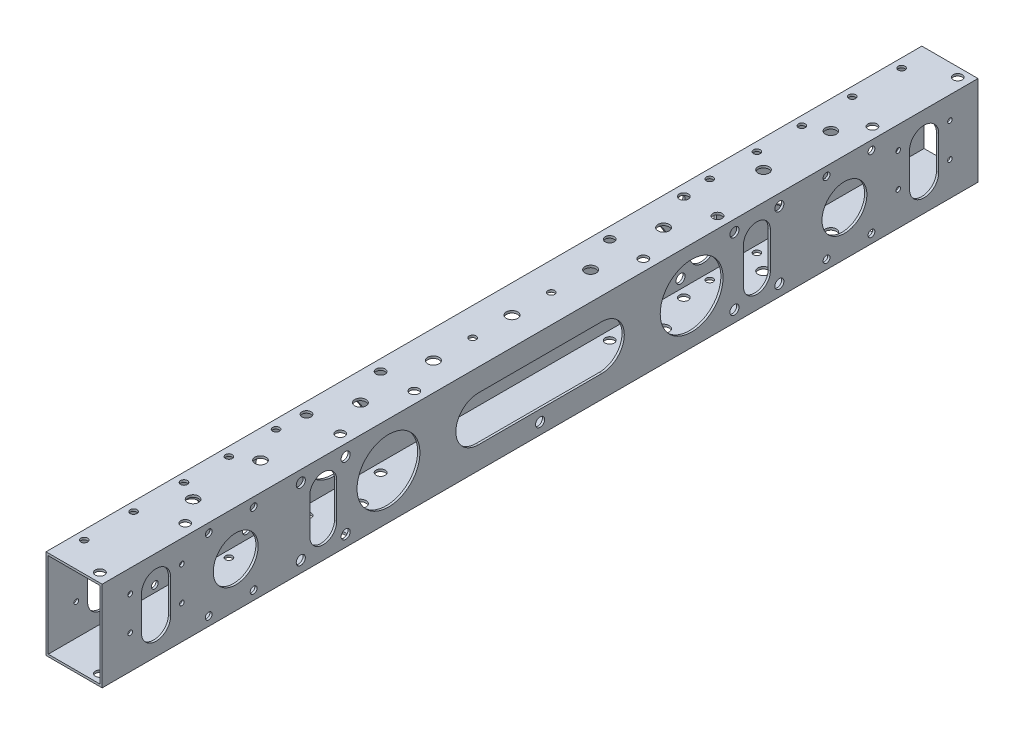
SolidWorks part; units mm, degrees
material "6061 合金"
ref_plane "前视基准面" through (0, 0, 0) normal (0, 0, 1) x (1, 0, 0)
ref_plane "上视基准面" through (0, 0, 0) normal (0, 1, 0) x (1, 0, 0)
ref_plane "右视基准面" through (0, 0, 0) normal (1, 0, 0) x (0, 0, -1)
other "Configuration Table"
sketch "草图1" plane through (0, 0, 0) normal (0, 0, 1) x (1, 0, 0)
  line L0 (-11.5, -19) -> (-11.5, 19)
  line L1 (-12.5, -20) -> (12.5, -20)
  line L2 (-12.5, -20) -> (-12.5, 20)
  line L3 (-12.5, 20) -> (12.5, 20)
  line L4 (12.5, -20) -> (12.5, 20)
  line L5 (-12.5, -20) -> (12.5, 20) construction
  line L6 (-12.5, 20) -> (12.5, -20) construction
  line L7 (-11.5, 19) -> (11.5, 19)
  line L8 (11.5, -19) -> (11.5, 19)
  line L9 (-11.5, -19) -> (11.5, -19)
  point P0 (0, 0)
  dimension "D1" = 25
  dimension "D2" = 40
  dimension "D3" = 1
extrude "凸台-拉伸1" add sketch "草图1" along normal mid plane 390
sketch "草图3" plane through (12.5, 0, 0) normal (1, 0, 0) x (0, 0, -1)
  circle A0 centre (67.5, 0) radius 12.5 construction
  circle A1 centre (67.5, 0) radius 12.5 construction
  circle A2 centre (-67.5, 0) radius 12.5 construction
  circle A3 centre (-67.5, 0) radius 12.5 construction
  circle A4 centre (-67.5, 0) radius 14
  circle A5 centre (67.5, 0) radius 14
  dimension "D1" = 1.5
extrude "切除-拉伸1" cut sketch "草图3" against normal mid plane 80
sketch "草图4" plane through (0, 20, 0) normal (0, 1, 0) x (1, 0, 0)
  line L0 (0, 0) -> (12.5, 0) construction
  line L1 (12.5, -195) -> (12.5, 195) construction
  circle A0 centre (-7.5, -84) radius 1.65 construction
  circle A1 centre (-7.5, -51) radius 1.65 construction
  circle A2 centre (-7.5, -84) radius 1.65 construction
  circle A3 centre (-7.5, -51) radius 1.65 construction
  circle A6 centre (-7.5, -51) radius 2.025
  circle A7 centre (-7.5, -84) radius 2.025
  circle A8 centre (-7.5, 51) radius 1.65 construction
  circle A9 centre (-7.5, 84) radius 1.65 construction
  circle A10 centre (-7.5, 84) radius 2.025
  circle A11 centre (-7.5, 51) radius 2.025
  dimension "D1" = 4.05
extrude "切除-拉伸2" cut sketch "草图4" against normal mid plane 150
mirror "镜向1" about plane through (0, 0, 0) normal (1, 0, 0) of "切除-拉伸2"
sketch "草图5" plane through (0, 20, 0) normal (0, 1, 0) x (1, 0, 0)
  line L0 (7.5, 84) -> (-7.5, 51) construction
  line L1 (0, 0) -> (12.5, 0) construction
  line L2 (12.5, -195) -> (12.5, 195) construction
  circle A0 centre (0, 67.5) radius 2.5
  circle A1 centre (0, -67.5) radius 2.5
  dimension "D1" = 5
extrude "切除-拉伸3" cut sketch "草图5" against normal mid plane 110
sketch "草图6" plane through (12.5, 0, 0) normal (1, 0, 0) x (0, 0, -1)
  line L0 (0, 0) -> (0, -34.3238) construction
  circle A0 centre (106.55, -14.95) radius 1.65 construction
  circle A1 centre (86.55, -14.95) radius 1.65 construction
  circle A2 centre (86.55, 14.95) radius 1.65 construction
  circle A3 centre (106.55, 14.95) radius 1.65 construction
  circle A4 centre (106.55, -14.95) radius 1.65 construction
  circle A5 centre (86.55, -14.95) radius 1.65 construction
  circle A6 centre (86.55, 14.95) radius 1.65 construction
  circle A7 centre (106.55, 14.95) radius 1.65 construction
  circle A8 centre (86.55, -14.95) radius 2.025
  circle A9 centre (86.55, 14.95) radius 2.025
  circle A10 centre (106.55, 14.95) radius 2.025
  circle A11 centre (106.55, -14.95) radius 2.025
  circle A12 centre (-106.55, 14.95) radius 1.65 construction
  circle A13 centre (-86.55, 14.95) radius 1.65 construction
  circle A14 centre (-86.55, -14.95) radius 1.65 construction
  circle A15 centre (-106.55, -14.95) radius 1.65 construction
  circle A16 centre (-106.55, -14.95) radius 2.025
  circle A17 centre (-106.55, 14.95) radius 2.025
  circle A18 centre (-86.55, 14.95) radius 2.025
  circle A19 centre (-86.55, -14.95) radius 2.025
  dimension "D1" = 4.05
extrude "切除-拉伸4" cut sketch "草图6" against normal blind 90
sketch "草图7" [suppressed] plane through (0, 20, 0) normal (0, 1, 0) x (1, 0, 0)
  line L0 (0, 0) -> (46.4595, 0) construction
  circle A0 centre (8.5, 96.55) radius 1.25 construction
  circle A1 centre (8.5, 96.55) radius 1.25 construction
  circle A2 centre (8.5, 96.55) radius 1.525
  circle A3 centre (8.5, -96.55) radius 1.25 construction
  circle A4 centre (8.5, -96.55) radius 1.525
  dimension "D1" = 3.05
extrude "切除-拉伸5" [suppressed] cut sketch "草图7" against normal blind 140
sketch "草图8" plane through (0, 20, 0) normal (0, 1, 0) x (1, 0, 0)
  line L0 (0, 0) -> (49.5268, 0) construction
  circle A0 centre (-8.5, 96.55) radius 1.25 construction
  circle A1 centre (-8.5, 96.55) radius 1.25 construction
  circle A2 centre (-8.5, 96.55) radius 1.525
  circle A3 centre (-8.5, -96.55) radius 1.25 construction
  circle A4 centre (-8.5, -96.55) radius 1.525
  dimension "D1" = 3.05
extrude "切除-拉伸6" cut sketch "草图8" against normal blind 140
sketch "草图9" plane through (12.5, 0, 0) normal (1, 0, 0) x (0, 0, -1)
  line L0 (86.55, 14.95) -> (106.55, -14.95) construction
  line L1 (96.55, -8) -> (96.55, 8) construction
  line L2 (90.55, -8) -> (90.55, 8)
  line L3 (102.55, -8) -> (102.55, 8)
  line L4 (67.5, 14) -> (96.55, 14) construction
  arc A1 (90.55, -8) -> (102.55, -8) centre (96.55, -8) ccw
  arc A2 (102.55, 8) -> (90.55, 8) centre (96.55, 8) ccw
  circle A3 centre (67.5, 0) radius 14 construction
  point P6 (96.55, 0)
  dimension "D1" = 4
extrude "切除-拉伸7" cut sketch "草图9" against normal blind 140
mirror "镜向2" about plane through (0, 0, 0) normal (0, 0, 1) of "切除-拉伸7"
sketch "草图11" plane through (11.5, 0, 0) normal (-1, 0, 0) x (0, 0, 1)
  line L0 (0, 0) -> (0, 48.4745) construction
  circle A0 centre (159.5, -5) radius 1.025 construction
  circle A1 centre (159.5, 10) radius 1.025 construction
  circle A2 centre (182.5, -5) radius 1.025 construction
  circle A3 centre (182.5, 10) radius 1.025 construction
  circle A4 centre (159.5, -5) radius 1.025
  circle A5 centre (159.5, 10) radius 1.025
  circle A6 centre (182.5, -5) radius 1.025
  circle A7 centre (182.5, 10) radius 1.025
  circle A8 centre (-182.5, 10) radius 1.025
  circle A9 centre (-182.5, -5) radius 1.025
  circle A10 centre (-159.5, 10) radius 1.025
  circle A11 centre (-159.5, -5) radius 1.025
extrude "切除-拉伸8" cut sketch "草图11" against normal blind 96
sketch "草图13" plane through (-11.5, 0, 0) normal (1, 0, 0) x (0, 0, -1)
  circle A1 centre (-182.5, 10) radius 1.025
  circle A2 centre (-182.5, 10) radius 1.025
  circle A3 centre (-182.5, -5) radius 1.025
  circle A4 centre (-182.5, -5) radius 1.025
  circle A5 centre (-159.5, 10) radius 1.025
  circle A6 centre (-159.5, 10) radius 1.025
  circle A7 centre (-159.5, -5) radius 1.025
  circle A8 centre (-159.5, -5) radius 1.025
  circle A9 centre (159.5, -5) radius 1.025
  circle A10 centre (159.5, -5) radius 1.025
  circle A11 centre (159.5, 10) radius 1.025
  circle A12 centre (159.5, 10) radius 1.025
  circle A13 centre (182.5, -5) radius 1.025
  circle A14 centre (182.5, -5) radius 1.025
  circle A15 centre (182.5, 10) radius 1.025
  circle A16 centre (182.5, 10) radius 1.025
  dimension "D1" = 0
  dimension "D2" = 0
  dimension "D3" = 0
  dimension "D4" = 0
  dimension "D5" = 0
  dimension "D6" = 0
  dimension "D7" = 0
  dimension "D8" = 0
extrude "切除-拉伸9" cut sketch "草图13" against normal blind 96
sketch "草图14" plane through (0, 20, 0) normal (0, 1, 0) x (1, 0, 0)
  line L0 (0, 0) -> (39.6162, 0) construction
  circle A0 centre (-8.5, -182) radius 1.25 construction
  circle A1 centre (-8.5, -160) radius 1.25 construction
  circle A2 centre (-8.5, -182) radius 1.25 construction
  circle A3 centre (-8.5, -160) radius 1.25 construction
  circle A4 centre (-8.5, -160) radius 1.525
  circle A5 centre (-8.5, -182) radius 1.525
  circle A6 centre (-8.5, 160) radius 1.25 construction
  circle A7 centre (-8.5, 182) radius 1.25 construction
  circle A8 centre (-8.5, 182) radius 1.525
  circle A9 centre (-8.5, 160) radius 1.525
  dimension "D1" = 3.05
extrude "切除-拉伸10" cut sketch "草图14" against normal mid plane 66
sketch "草图16" plane through (-12.5, 0, 0) normal (-1, 0, 0) x (0, 0, 1)
  line L0 (159.5, 10) -> (182.5, 10) construction
  line L1 (171, 20) -> (171, -20) construction
  line L2 (195, 20) -> (-195, 20) construction
  line L3 (195, -20) -> (-195, -20) construction
  line L4 (171, -7.5) -> (171, 7.5) construction
  line L5 (164.5, -7.5) -> (164.5, 7.5)
  line L6 (177.5, -7.5) -> (177.5, 7.5)
  line L7 (96.55, 14) -> (171, 14) construction
  arc A0 (164.5, -7.5) -> (177.5, -7.5) centre (171, -7.5) ccw
  arc A1 (177.5, 7.5) -> (164.5, 7.5) centre (171, 7.5) ccw
  arc A2 (102.55, 8) -> (90.55, 8) centre (96.55, 8) ccw construction
  circle A3 centre (182.5, 10) radius 1.025 construction
  point P10 (171, 10)
  point P13 (171, 0)
  dimension "D1" = 5
extrude "切除-拉伸12" cut sketch "草图16" against normal mid plane 66
sketch "草图15" [suppressed] plane through (0, 20, 0) normal (0, 1, 0) x (1, 0, 0)
  line L0 (0, 0) -> (85.0224, 0) construction
  circle A0 centre (8.5, -182) radius 1.25 construction
  circle A1 centre (8.5, -160) radius 1.25 construction
  circle A2 centre (8.5, -182) radius 1.25 construction
  circle A3 centre (8.5, -160) radius 1.25 construction
  circle A4 centre (8.5, -160) radius 1.525
  circle A5 centre (8.5, -182) radius 1.525
  circle A6 centre (8.5, 160) radius 1.25 construction
  circle A7 centre (8.5, 182) radius 1.25 construction
  circle A8 centre (8.5, 182) radius 1.525
  circle A9 centre (8.5, 160) radius 1.525
  dimension "D1" = 3.05
extrude "切除-拉伸11" [suppressed] cut sketch "草图15" against normal mid plane 106
mirror "镜向3" about plane through (0, 0, 0) normal (0, 0, 1) of "切除-拉伸12"
sketch "草图17" plane through (12.5, 0, 0) normal (1, 0, 0) x (0, 0, -1)
  line L0 (-182.5, 10) -> (-159.5, 10) construction
  line L1 (-171, 20) -> (-171, -20) construction
  line L2 (-195, 20) -> (195, 20) construction
  line L3 (-195, -20) -> (195, -20) construction
  line L4 (-171, -7.5) -> (-171, 7.5) construction
  line L5 (-177.5, -7.5) -> (-177.5, 7.5)
  line L6 (-164.5, -7.5) -> (-164.5, 7.5)
  line L7 (-171, 14) -> (-96.55, 14) construction
  arc A0 (-177.5, -7.5) -> (-164.5, -7.5) centre (-171, -7.5) ccw
  arc A1 (-164.5, 7.5) -> (-177.5, 7.5) centre (-171, 7.5) ccw
  arc A2 (-90.55, 8) -> (-102.55, 8) centre (-96.55, 8) ccw construction
  circle A3 centre (-159.5, 10) radius 1.025 construction
  point P10 (-171, 10)
  point P13 (-171, 0)
  dimension "D1" = 5
extrude "切除-拉伸13" [suppressed] cut sketch "草图17" against normal mid plane 66
mirror "镜向4" [suppressed] about plane through (0, 0, 0) normal (0, 0, 1)
sketch "草图18" [suppressed] plane through (0, 20, 0) normal (0, 1, 0) x (1, 0, 0)
  line L0 (0, 0) -> (38.8845, 0) construction
  circle A0 centre (-7.5, -191) radius 1.65 construction
  circle A1 centre (-7.5, -153) radius 1.65 construction
  circle A2 centre (-7.5, -191) radius 1.65 construction
  circle A3 centre (-7.5, -153) radius 1.65 construction
  circle A4 centre (-7.5, -153) radius 2.025
  circle A5 centre (-7.5, -191) radius 2.025
  circle A6 centre (-7.5, 153) radius 1.65 construction
  circle A7 centre (-7.5, 191) radius 1.65 construction
  circle A8 centre (-7.5, 191) radius 2.025
  circle A9 centre (-7.5, 153) radius 2.025
  dimension "D1" = 4.05
extrude "切除-拉伸14" [suppressed] cut sketch "草图18" against normal mid plane 160
sketch "草图19" plane through (0, 20, 0) normal (0, 1, 0) x (1, 0, 0)
  line L0 (0, 0) -> (45.5725, 0) construction
  circle A0 centre (7.5, -191) radius 1.65 construction
  circle A1 centre (7.5, -153) radius 1.65 construction
  circle A2 centre (7.5, -191) radius 1.65 construction
  circle A3 centre (7.5, -153) radius 1.65 construction
  circle A4 centre (7.5, -153) radius 2.025
  circle A5 centre (7.5, -191) radius 2.025
  circle A6 centre (7.5, 153) radius 1.65 construction
  circle A7 centre (7.5, 191) radius 1.65 construction
  circle A8 centre (7.5, 191) radius 2.025
  circle A9 centre (7.5, 153) radius 2.025
  dimension "D1" = 4.05
extrude "切除-拉伸15" cut sketch "草图19" against normal mid plane 160
sketch "草图20" plane through (0, -20, 0) normal (0, -1, 0) x (1, 0, 0)
  line L0 (0, 0) -> (32.6332, 0) construction
  circle A0 centre (0, 112) radius 1.525 construction
  circle A1 centre (0, 142) radius 1.525 construction
  circle A2 centre (0, 112) radius 1.525 construction
  circle A3 centre (0, 142) radius 1.525 construction
  circle A4 centre (0, 142) radius 2.475
  circle A5 centre (0, 112) radius 2.475
  circle A6 centre (0, -142) radius 1.525 construction
  circle A7 centre (0, -112) radius 1.525 construction
  circle A8 centre (0, -112) radius 2.475
  circle A9 centre (0, -142) radius 2.475
  dimension "D1" = 4.95
extrude "切除-拉伸16" cut sketch "草图20" against normal blind 80
sketch "草图21" [suppressed] plane through (0, 20, 0) normal (0, 1, 0) x (1, 0, 0)
  circle A0 centre (0, 35) radius 2.525 construction
  circle A1 centre (0, 0) radius 2.525 construction
  circle A2 centre (0, -35) radius 2.525 construction
  circle A3 centre (0, 35) radius 2.525
  circle A4 centre (0, 0) radius 2.525
  circle A5 centre (0, -35) radius 2.525
sketch "草图22" plane through (0, 20, 0) normal (0, 1, 0) x (1, 0, 0)
  circle A0 centre (0, 35) radius 2.525 construction
  circle A1 centre (0, 0) radius 2.525 construction
  circle A2 centre (0, -35) radius 2.525 construction
  circle A3 centre (0, 35) radius 2.525
  circle A4 centre (0, 0) radius 2.525
  circle A5 centre (0, -35) radius 2.525
extrude "切除-拉伸17" [suppressed] cut sketch "草图21" against normal blind 10
extrude "切除-拉伸18" cut sketch "草图22" against normal blind 10
sketch "草图24" [suppressed] plane through (0, 20, 0) normal (0, 1, 0) x (1, 0, 0)
  line L0 (0, 35) -> (0, 0) construction
  line L1 (0, 0) -> (0, -35) construction
  circle A0 centre (0, 17.5) radius 1.525
  circle A1 centre (0, -17.5) radius 1.525
  dimension "D1" = 3.05
extrude "切除-拉伸19" [suppressed] cut sketch "草图24" against normal blind 16
sketch "草图25" plane through (0, 20, 0) normal (0, 1, 0) x (1, 0, 0)
  line L0 (0, 35) -> (0, 0) construction
  line L1 (0, 0) -> (0, -35) construction
  circle A0 centre (0, 17.5) radius 1.525
  circle A1 centre (0, -17.5) radius 1.525
  dimension "D1" = 3.05
extrude "切除-拉伸20" cut sketch "草图25" against normal blind 16
sketch "草图26" plane through (12.5, 0, 0) normal (1, 0, 0) x (0, 0, -1)
  line L0 (-27.5, 0) -> (27.5, 0) construction
  line L1 (-27.5, 10) -> (27.5, 10)
  line L2 (-27.5, -10) -> (27.5, -10)
  arc A0 (-27.5, 10) -> (-27.5, -10) centre (-27.5, 0) ccw
  arc A1 (27.5, -10) -> (27.5, 10) centre (27.5, 0) ccw
  point P2 (0, 0)
  dimension "D1" = 20
  dimension "D2" = 55
extrude "切除-拉伸21" cut sketch "草图26" against normal blind 86
sketch "草图27" plane through (0, -20, 0) normal (0, -1, 0) x (1, 0, 0)
  circle A0 centre (7.5, -15) radius 2.1 construction
  circle A1 centre (7.5, 15) radius 2.1 construction
  circle A2 centre (7.5, -15) radius 2.1 construction
  circle A3 centre (7.5, 15) radius 2.1 construction
  circle A4 centre (7.5, 15) radius 2.025
  circle A5 centre (7.5, -15) radius 2.025
  dimension "D1" = 4.05
sketch "草图28" [suppressed] plane through (0, -20, 0) normal (0, -1, 0) x (1, 0, 0)
  circle A0 centre (-7.5, -15) radius 2.1 construction
  circle A1 centre (-7.5, 15) radius 2.1 construction
  circle A2 centre (-7.5, -15) radius 2.1 construction
  circle A3 centre (-7.5, 15) radius 2.1 construction
  circle A4 centre (-7.5, 15) radius 2.025
  circle A5 centre (-7.5, -15) radius 2.025
  dimension "D1" = 4.05
extrude "切除-拉伸22" cut sketch "草图27" against normal blind 10
extrude "切除-拉伸23" [suppressed] cut sketch "草图28" against normal blind 10
sketch "草图29" [suppressed] plane through (-12.5, 0, 0) normal (-1, 0, 0) x (0, 0, 1)
  line L0 (-106.55, 14.95) -> (-106.55, -14.95) construction
  line L1 (-164.5, 0) -> (-106.55, 0) construction
  line L2 (-164.5, -7.5) -> (-164.5, 7.5) construction
  circle A0 centre (-135.525, 0) radius 10
  dimension "D1" = 20
extrude "切除-拉伸24" [suppressed] cut sketch "草图29" against normal blind 78
mirror "镜向5" [suppressed] about plane through (0, 0, 0) normal (0, 0, 1)
sketch "草图30" plane through (12.5, 0, 0) normal (1, 0, 0) x (0, 0, -1)
  circle A1 centre (135.525, 0) radius 10
  circle A2 centre (135.525, 0) radius 10
  dimension "D1" = 0
extrude "切除-拉伸25" cut sketch "草图30" against normal blind 78
mirror "镜向6" about plane through (0, 0, 0) normal (0, 0, 1) of "切除-拉伸25"
sketch "草图31" [suppressed] plane through (0, 20, 0) normal (0, 1, 0) x (1, 0, 0)
  line L0 (0, 0) -> (37.8441, 0) construction
  circle A0 centre (8.5, -137.55) radius 1.25 construction
  circle A1 centre (8.5, -117.55) radius 1.25 construction
  circle A2 centre (8.5, -137.55) radius 1.25 construction
  circle A3 centre (8.5, -117.55) radius 1.25 construction
  circle A4 centre (8.5, -117.55) radius 1.525
  circle A5 centre (8.5, -137.55) radius 1.525
  circle A6 centre (8.5, 117.55) radius 1.25 construction
  circle A7 centre (8.5, 137.55) radius 1.25 construction
  circle A8 centre (8.5, 137.55) radius 1.525
  circle A9 centre (8.5, 117.55) radius 1.525
  dimension "D1" = 3.05
sketch "草图32" [suppressed] plane through (12.5, 0, 0) normal (1, 0, 0) x (0, 0, -1)
  line L0 (0, 0) -> (-199.2952, 0) construction
  circle A0 centre (-147.55, 16) radius 1.25 construction
  circle A1 centre (-127.55, 16) radius 1.25 construction
  circle A2 centre (-147.55, 16) radius 1.25 construction
  circle A3 centre (-127.55, 16) radius 1.25 construction
  circle A4 centre (-147.55, 16) radius 1.525
  circle A5 centre (-127.55, 16) radius 1.525
  circle A6 centre (-127.55, -16) radius 1.25 construction
  circle A7 centre (-147.55, -16) radius 1.25 construction
  circle A8 centre (-127.55, -16) radius 1.525
  circle A9 centre (-147.55, -16) radius 1.525
  dimension "D1" = 3.05
extrude "切除-拉伸26" [suppressed] cut sketch "草图31" against normal blind 78
extrude "切除-拉伸27" [suppressed] cut sketch "草图32" against normal blind 78
mirror "镜向7" [suppressed] about plane through (0, 0, 0) normal (0, 0, 1)
sketch "草图33" plane through (0, 20, 0) normal (0, 1, 0) x (1, 0, 0)
  line L0 (0, 0) -> (12.5, 0) construction
  line L1 (12.5, -195) -> (12.5, 195) construction
  circle A0 centre (-8.5, -137.55) radius 1.25 construction
  circle A1 centre (-8.5, -117.55) radius 1.25 construction
  circle A2 centre (-8.5, -137.55) radius 1.25 construction
  circle A3 centre (-8.5, -117.55) radius 1.25 construction
  circle A4 centre (-8.5, -117.55) radius 1.525
  circle A5 centre (-8.5, -137.55) radius 1.525
  circle A6 centre (-8.5, 117.55) radius 1.25 construction
  circle A7 centre (-8.5, 137.55) radius 1.25 construction
  circle A8 centre (-8.5, 137.55) radius 1.525
  circle A9 centre (-8.5, 117.55) radius 1.525
  dimension "D1" = 3.05
sketch "草图34" plane through (-12.5, 0, 0) normal (-1, 0, 0) x (0, 0, 1)
  line L0 (0, 0) -> (240.6441, 0) construction
  circle A0 centre (147.55, 16) radius 1.25 construction
  circle A1 centre (127.55, 16) radius 1.25 construction
  circle A2 centre (147.55, 16) radius 1.25 construction
  circle A3 centre (127.55, 16) radius 1.25 construction
  circle A4 centre (127.55, 16) radius 1.525
  circle A5 centre (147.55, 16) radius 1.525
  circle A6 centre (127.55, -16) radius 1.25 construction
  circle A7 centre (147.55, -16) radius 1.25 construction
  circle A8 centre (147.55, -16) radius 1.525
  circle A9 centre (127.55, -16) radius 1.525
  dimension "D1" = 3.05
extrude "切除-拉伸28" cut sketch "草图33" against normal blind 78
extrude "切除-拉伸29" cut sketch "草图34" against normal blind 78
mirror "镜向8" about plane through (0, 0, 0) normal (0, 0, 1) of "切除-拉伸29"
sketch "草图35" plane through (12.5, 0, 0) normal (1, 0, 0) x (0, 0, -1)
  circle A0 centre (0, -15) radius 1.65 construction
  circle A1 centre (0, -15) radius 1.65 construction
  circle A2 centre (0, -15) radius 2.025
  dimension "D1" = 4.05
extrude "切除-拉伸30" cut sketch "草图35" against normal mid plane 10
sketch "草图36" [suppressed] plane through (-12.5, 0, 0) normal (-1, 0, 0) x (0, 0, 1)
  circle A0 centre (0, -15) radius 1.65 construction
  circle A1 centre (0, -15) radius 1.65 construction
  circle A2 centre (0, -15) radius 2.025
  dimension "D1" = 4.05
extrude "切除-拉伸31" [suppressed] cut sketch "草图36" against normal mid plane 10
